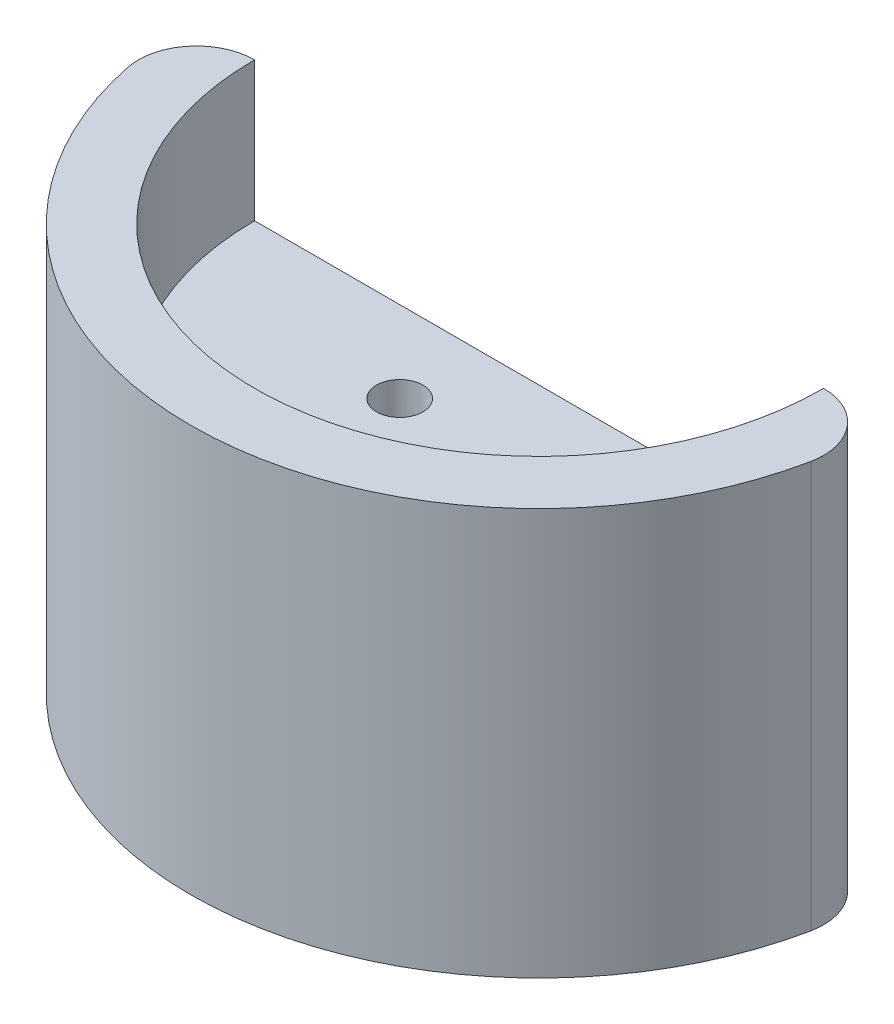
SolidWorks part; units mm, degrees
ref_plane "Front Plane" through (0, 0, 0) normal (0, 0, 1) x (1, 0, 0)
ref_plane "Top Plane" through (0, 0, 0) normal (0, 1, 0) x (1, 0, 0)
ref_plane "Right Plane" through (0, 0, 0) normal (1, 0, 0) x (0, 0, -1)
sketch "Sketch4" plane through (0, 0, 0) normal (0, 1, 0) x (1, 0, 0)
  line L0 (-57.4787, 14.2038) -> (-47.4787, 14.2038)
  line L1 (-17.4787, 14.2038) -> (2.5213, 14.2038)
  arc A0 (-17.4787, 14.2038) -> (-47.4787, 14.2038) centre (-32.4787, 14.2038) cw
  arc A2 (2.5213, 14.2038) -> (-57.4787, 14.2038) centre (-27.4787, 14.2038) cw
  dimension "D1" = 15
  dimension "D2" = 30
  dimension "D3" = 10
extrude "Boss-Extrude1" add sketch "Sketch4" along normal blind 5
sketch "Sketch5" plane through (0, 5, 0) normal (0, 1, 0) x (1, 0, 0)
  line L0 (-57.4787, 14.2038) -> (2.5213, 14.2038)
  arc A0 (-57.4787, 14.2038) -> (2.5213, 14.2038) centre (-27.4787, 14.2038) ccw
  arc A1 (-57.4787, 14.2038) -> (2.5213, 14.2038) centre (-27.4787, 14.2038) ccw construction
extrude "Boss-Extrude2" add sketch "Sketch5" along normal blind 15
sketch "Sketch6" plane through (0, 0, 0) normal (0, -1, 0) x (1, 0, 0)
  line L0 (-47.4787, -14.2038) -> (-57.4787, -14.2038) construction
  line L1 (2.5213, -14.2038) -> (-57.4787, -14.2038)
  arc A0 (2.5213, -14.2038) -> (-57.4787, -14.2038) centre (-27.4787, -14.2038) ccw
extrude "Boss-Extrude3" add sketch "Sketch6" along normal blind 15
fillet "Fillet2" radius 5 1 edges at (2.5213, 2.5, -14.2038)
fillet "Fillet3" radius 5 1 edges at (-57.4787, 2.5, -14.2038)
sketch "Sketch8" plane through (0, 20, 0) normal (0, 1, 0) x (1, 0, 0)
  line L0 (-2.9838, 14.2038) -> (-51.9736, 14.2038) construction
  line L1 (-51.9736, 14.2038) -> (-2.9838, 14.2038)
  arc A0 (-2.9838, 14.2038) -> (-51.9736, 14.2038) centre (-27.4787, 14.2038) cw
extrude "Cut-Extrude1" cut sketch "Sketch8" against normal blind 12
sketch "Sketch9" plane through (0, -15, 0) normal (0, -1, 0) x (1, 0, 0)
  line L0 (-51.9736, -14.2038) -> (-2.9838, -14.2038) construction
  line L1 (-51.9736, -14.2038) -> (-2.9838, -14.2038)
  arc A0 (-51.9736, -14.2038) -> (-2.9838, -14.2038) centre (-27.4787, -14.2038) cw
extrude "Cut-Extrude2" cut sketch "Sketch9" against normal blind 12
sketch "Sketch11" plane through (0, -3, 0) normal (0, -1, 0) x (1, 0, 0)
  line L0 (-17.4787, -14.2038) -> (-47.4787, -14.2038) construction
  line L1 (-51.9736, -14.2038) -> (-2.9838, -14.2038) construction
  circle A0 centre (-32.4787, -7.2038) radius 2
  point P7 (-32.4787, -14.2038)
  dimension "D1" = 4
  dimension "D2" = 7
extrude "Cut-Extrude3" cut sketch "Sketch11" against normal blind 11
